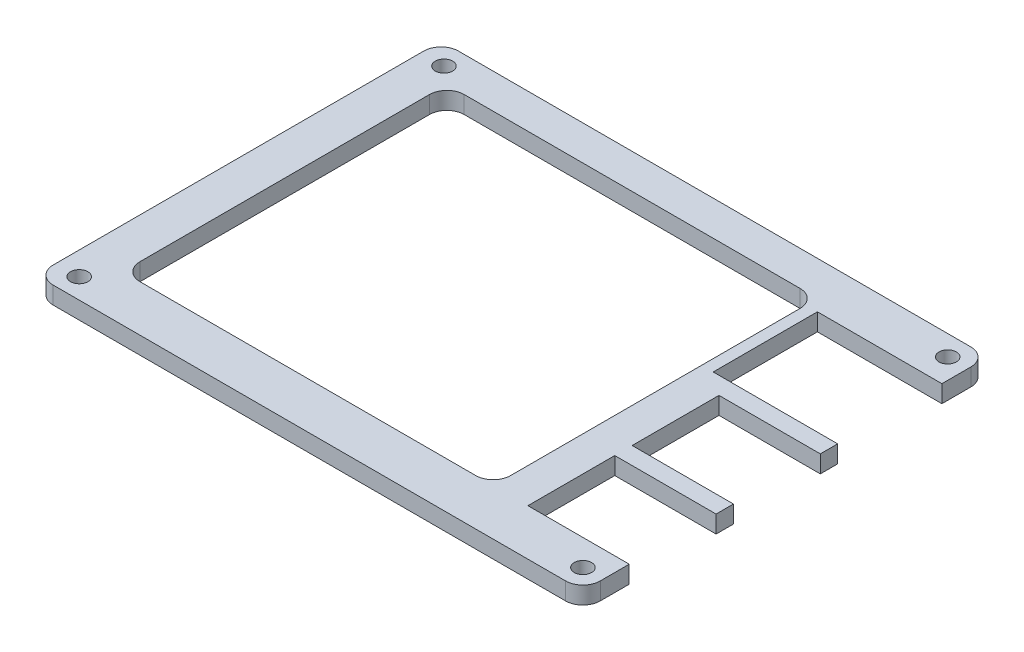
SolidWorks part; units mm, degrees
material "Balsa"
ref_plane "Front Plane" through (0, 0, 0) normal (0, 0, 1) x (1, 0, 0)
ref_plane "Top Plane" through (0, 0, 0) normal (0, 1, 0) x (1, 0, 0)
ref_plane "Right Plane" through (0, 0, 0) normal (1, 0, 0) x (0, 0, -1)
sketch "Sketch1" plane through (0, 0, 0) normal (0, 1, 0) x (1, 0, 0)
  line L1 (-47.25, 35) -> (47.25, 35)
  line L2 (-47.25, 35) -> (-47.25, -35)
  line L3 (-47.25, -35) -> (47.25, -35)
  line L4 (47.25, 35) -> (47.25, -35)
  line L5 (-47.25, 35) -> (47.25, -35) construction
  line L6 (-47.25, -35) -> (47.25, 35) construction
  point P0 (0, 0)
  dimension "D1" = 70
  dimension "D2" = 94.5
extrude "Boss-Extrude1" add sketch "Sketch1" along normal blind 3
sketch "Sketch3" plane through (0, 3, 0) normal (0, 1, 0) x (1, 0, 0)
  line L0 (47.25, -35) -> (47.25, 35) construction
  line L2 (47.25, 35) -> (-47.25, 35) construction
  circle A0 centre (43.75, 31.5) radius 1.5
  circle A1 centre (-43.25, 31.5) radius 1.5
  circle A2 centre (-43.25, -31.5) radius 1.5
  circle A3 centre (43.75, -31.5) radius 1.5
  dimension "D1" = 3
  dimension "D2" = 3.5
  dimension "D3" = 3.5
  dimension "D4" = 2
  dimension "D5" = 87
  dimension "D6" = 63
  dimension "D7" = 2
extrude "Cut-Extrude2" cut sketch "Sketch3" against normal through all
fillet "Fillet2" radius 3 4 edges at (-47.25, 1.5, 35) (-47.25, 1.5, -35) (47.25, 1.5, -35) (47.25, 1.5, 35)
sketch "Sketch5" plane through (0, 3, 0) normal (0, 1, 0) x (1, 0, 0)
  line L0 (-40.25, 29) -> (23.75, 29)
  line L1 (23.75, 29) -> (23.75, -27)
  line L2 (23.75, -27) -> (-40.25, -27)
  line L3 (-40.25, -27) -> (-40.25, 29)
  line L4 (47.25, 27) -> (25.75, 27)
  line L5 (47.25, -32) -> (47.25, 32) construction
  line L6 (25.75, 27) -> (25.75, 9)
  line L7 (25.75, 9) -> (47.25, 9)
  line L8 (47.25, 9) -> (47.25, 27)
  line L9 (47.25, 6) -> (29.75, 6)
  line L10 (29.75, 6) -> (29.75, -9)
  line L11 (29.75, -9) -> (47.25, -9)
  line L12 (47.25, -9) -> (47.25, 6)
  line L13 (47.25, -12) -> (29.75, -12)
  line L14 (29.75, -12) -> (29.75, -27)
  line L15 (29.75, -27) -> (47.25, -27)
  line L16 (47.25, -27) -> (47.25, -12)
  line L17 (44.25, 35) -> (-44.25, 35) construction
  line L18 (-47.25, 32) -> (-47.25, -32) construction
  dimension "D1" = 6
  dimension "D2" = 7
  dimension "D3" = 64
  dimension "D4" = 56
  dimension "D5" = 18
  dimension "D6" = 2
  dimension "D7" = 6
  dimension "D8" = 3
  dimension "D9" = 8
  dimension "D10" = 15
  dimension "D11" = 3
  dimension "D12" = 15
  dimension "D13" = 6
extrude "Cut-Extrude3" cut sketch "Sketch5" against normal through all
fillet "Fillet3" radius 3 4 edges at (23.75, 1.5, -29) (23.75, 1.5, 27) (-40.25, 1.5, 27) (-40.25, 1.5, -29)
